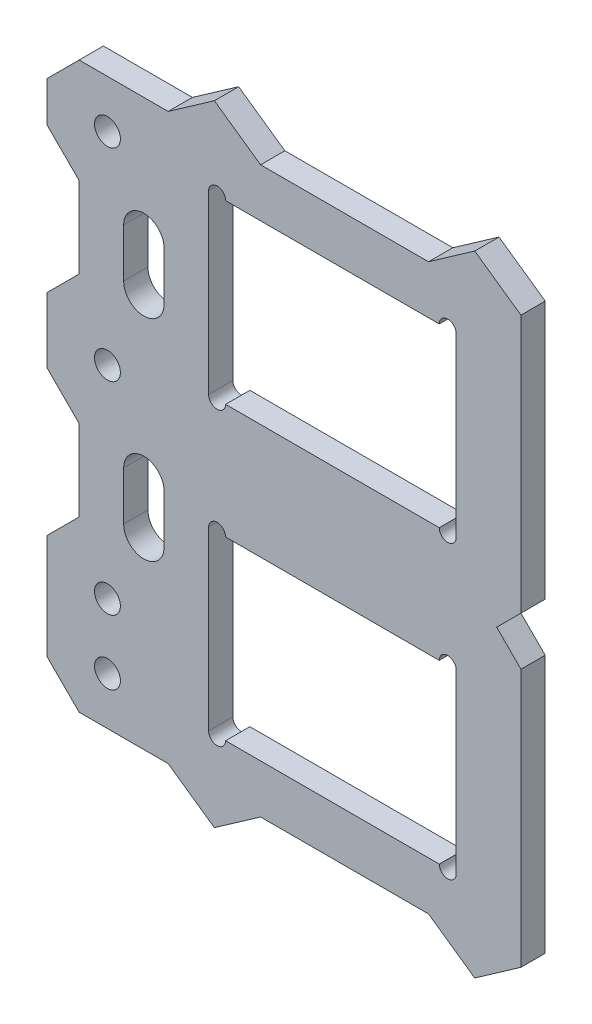
SolidWorks part; units mm, degrees
material "Thornel Mat VMA"
ref_plane "前视基准面" through (0, 0, 0) normal (0, 0, 1) x (1, 0, 0)
ref_plane "上视基准面" through (0, 0, 0) normal (0, 1, 0) x (1, 0, 0)
ref_plane "右视基准面" through (0, 0, 0) normal (1, 0, 0) x (0, 0, -1)
sketch "草图1" plane through (0, 0, 0) normal (0, 0, 1) x (1, 0, 0)
  line L0 (-4.479, -18) -> (14.342, -18) construction
  line L1 (15.3, -10.9) -> (-15.3, -10.9)
  line L2 (15.3, -10.9) -> (15.3, 10.9)
  line L3 (15.3, 10.9) -> (-15.3, 10.9)
  line L4 (-15.3, -10.9) -> (-15.3, 10.9)
  line L5 (15.3, -10.9) -> (-15.3, 10.9) construction
  line L6 (15.3, 10.9) -> (-15.3, -10.9) construction
  line L7 (15.3, -46.9) -> (-15.3, -46.9)
  line L8 (15.3, -46.9) -> (15.3, -25.1)
  line L9 (15.3, -25.1) -> (-15.3, -25.1)
  line L10 (-15.3, -46.9) -> (-15.3, -25.1)
  line L11 (15.3, -46.9) -> (-15.3, -25.1) construction
  line L12 (15.3, -25.1) -> (-15.3, -46.9) construction
  line L13 (-20.3, 11.2067) -> (-20.3, -47.2689) construction
  line L14 (-35.3, 16.9) -> (-20.3, 16.9)
  line L15 (23.3, 16.9) -> (23.3, -15)
  line L16 (11.8748, -52.9) -> (-8.8748, -52.9)
  line L17 (-35.3, -52.9) -> (-35.3, -36)
  line L18 (-20.3, 16.9) -> (-14.5874, 20.9)
  line L19 (-14.5874, 20.9) -> (-8.8748, 16.9)
  line L20 (11.8748, 16.9) -> (17.5874, 20.9)
  line L21 (17.5874, 20.9) -> (23.3, 16.9)
  line L22 (-8.8748, 16.9) -> (11.8748, 16.9)
  line L23 (17.5874, -56.9) -> (23.3, -52.9)
  line L24 (11.8748, -52.9) -> (17.5874, -56.9)
  line L25 (-14.5874, -56.9) -> (-8.8748, -52.9)
  line L26 (-20.3, -52.9) -> (-14.5874, -56.9)
  line L27 (-20.3, -52.9) -> (-35.3, -52.9)
  line L28 (23.3, -21) -> (20.3, -18)
  line L29 (20.3, -18) -> (23.3, -15)
  line L30 (23.3, -21) -> (23.3, -52.9)
  line L31 (-35.3, -36) -> (-31.3, -32)
  line L32 (-31.3, -32) -> (-31.3, -22)
  line L33 (-31.3, -22) -> (-35.3, -18)
  line L34 (-31.3, -27) -> (-36.8384, -27) construction
  line L35 (-35.3, -18) -> (-35.3, -10)
  line L36 (-27.8, -14) -> (-19.0378, -14) construction
  line L37 (-31.3, -6) -> (-35.3, -10)
  line L38 (-31.3, 4) -> (-31.3, -6)
  line L39 (-35.3, 8) -> (-31.3, 4)
  line L40 (-35.3, 8) -> (-35.3, 16.9)
  line L41 (-23.3, -30) -> (-23.3, -24) construction
  line L42 (-25.8, -30) -> (-25.8, -24)
  line L43 (-20.8, -30) -> (-20.8, -24)
  line L44 (-23.3, 2) -> (-23.3, -4) construction
  line L45 (-25.8, 2) -> (-25.8, -4)
  line L46 (-20.8, 2) -> (-20.8, -4)
  circle A0 centre (-27.8, -14) radius 1.6
  circle A1 centre (-27.8, -22) radius 1.6 construction
  circle A2 centre (-27.8, 11) radius 1.6
  circle A3 centre (-27.8, -47) radius 1.6
  circle A4 centre (14.25, 10.9) radius 1.05
  circle A5 centre (14.25, -10.9) radius 1.05
  circle A6 centre (-14.25, -10.9) radius 1.05
  circle A7 centre (-14.25, 10.9) radius 1.05
  circle A8 centre (14.25, -46.9) radius 1.05
  circle A9 centre (14.25, -25.1) radius 1.05
  circle A10 centre (-14.25, -25.1) radius 1.05
  circle A11 centre (-14.25, -46.9) radius 1.05
  circle A12 centre (-27.8, -39) radius 1.6
  arc A13 (-25.8, -30) -> (-20.8, -30) centre (-23.3, -30) ccw
  arc A14 (-20.8, -24) -> (-25.8, -24) centre (-23.3, -24) ccw
  arc A15 (-25.8, 2) -> (-20.8, 2) centre (-23.3, 2) cw
  arc A16 (-20.8, -4) -> (-25.8, -4) centre (-23.3, -4) cw
  point P0 (0, 0)
  point P6 (0, -36)
  point P69 (-23.3, -27)
  point P78 (-23.3, -1)
  dimension "D4" = 3.2
  dimension "D9" = 2.1
  dimension "D1" = 21.8
  dimension "D2" = 30.6
  dimension "D3" = 36
  dimension "D5" = 8
  dimension "D6" = 25
  dimension "D7" = 7.5
  dimension "D8" = 5
  dimension "D10" = 8
  dimension "D11" = 6
  dimension "D12" = 7.5
  dimension "D13" = 8
  dimension "D14" = 35
  dimension "D15" = 35
  dimension "D16" = 4
  dimension "D17" = 35
  dimension "D18" = 35
  dimension "D19" = 3
  dimension "D20" = 45
  dimension "D21" = 4
  dimension "D22" = 10
  dimension "D23" = 45
  dimension "D24" = 13
  dimension "D25" = 5
  dimension "D26" = 6
  dimension "D27" = 8
extrude "凸台-拉伸1" add sketch "草图1" along normal blind 3 contours L17 L16 L15 L14 A7 L3 A4 L2 A5 L1 A6 L4 A0 A1 A2 A3 L7 A11 L10 A10 L9 A9 L8 A8
chamfer "倒角1" distance 4 angle 45 2 edges at (-35.3, 16.9, 1.5) (-35.3, -52.9, 1.5)
